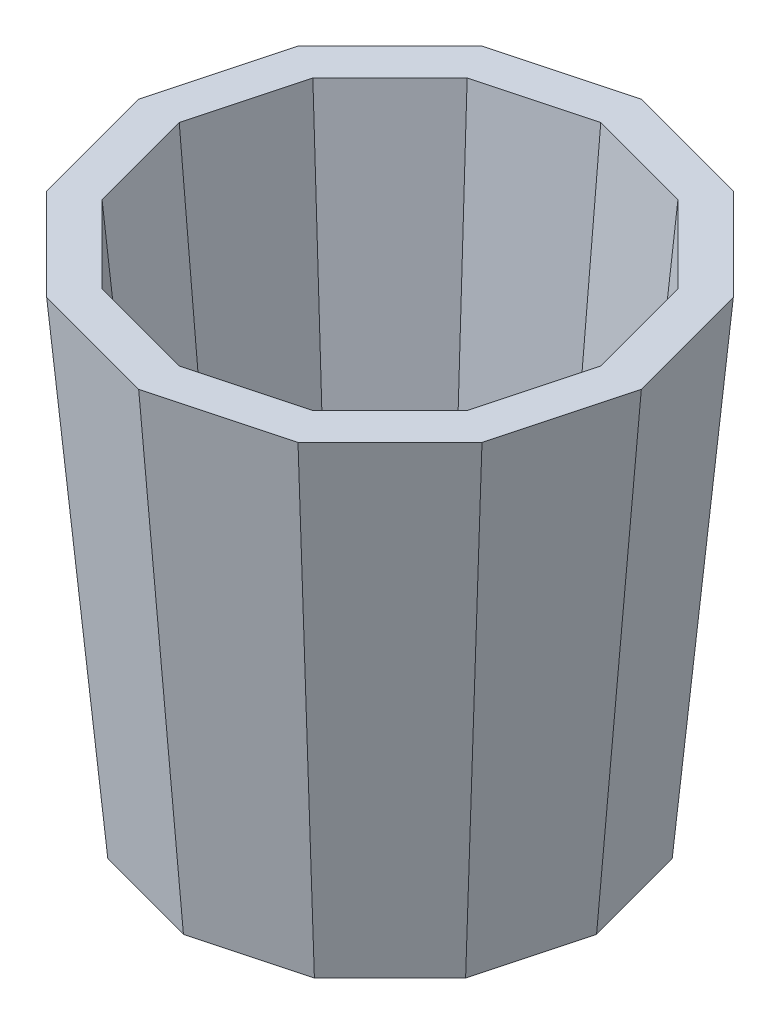
SolidWorks part; units mm, degrees
ref_plane "Front" through (0, 0, 0) normal (0, 0, 1) x (1, 0, 0)
ref_plane "Top" through (0, 0, 0) normal (0, 1, 0) x (1, 0, 0)
ref_plane "Right" through (0, 0, 0) normal (1, 0, 0) x (0, 0, -1)
sketch "Sketch1" plane through (0, 0, 0) normal (0, 1, 0) x (1, 0, 0)
  line L0 (122.6726, 0) -> (0, 0) construction
  line L1 (122.6726, 0) -> (106.2376, 61.3363)
  line L2 (106.2376, 61.3363) -> (61.3363, 106.2376)
  line L3 (61.3363, 106.2376) -> (0, 122.6726)
  line L4 (0, 122.6726) -> (-61.3363, 106.2376)
  line L5 (-61.3363, 106.2376) -> (-106.2376, 61.3363)
  line L6 (-106.2376, 61.3363) -> (-122.6726, 0)
  line L7 (-122.6726, 0) -> (-106.2376, -61.3363)
  line L8 (-106.2376, -61.3363) -> (-61.3363, -106.2376)
  line L9 (-61.3363, -106.2376) -> (0, -122.6726)
  line L10 (0, -122.6726) -> (61.3363, -106.2376)
  line L11 (61.3363, -106.2376) -> (106.2376, -61.3363)
  line L12 (106.2376, -61.3363) -> (122.6726, 0)
  circle A0 centre (0, 0) radius 118.4926 construction
  dimension "D1" = 63.5
extrude "Boss-Extrude1" add sketch "Sketch1" against normal blind 241.3 draft 5
shell "Shell1" thickness 19.05
